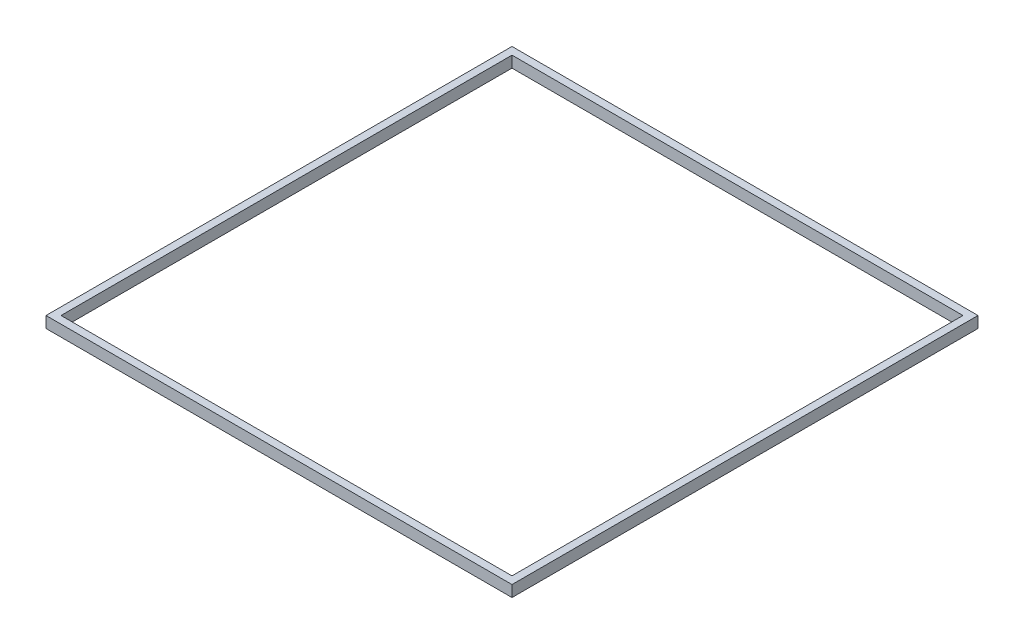
SolidWorks part; units mm, degrees
material "1060 Alloy"
ref_plane "Front Plane" through (0, 0, 0) normal (0, 0, 1) x (1, 0, 0)
ref_plane "Top Plane" through (0, 0, 0) normal (0, 1, 0) x (1, 0, 0)
ref_plane "Right Plane" through (0, 0, 0) normal (1, 0, 0) x (0, 0, -1)
sketch "Sketch1" plane through (0, 0, 0) normal (0, 1, 0) x (1, 0, 0)
  line L1 (-600, -600) -> (600, -600)
  line L2 (-600, -600) -> (-600, 600)
  line L3 (-600, 600) -> (600, 600)
  line L4 (600, -600) -> (600, 600)
  line L5 (-600, -600) -> (600, 600) construction
  line L6 (-600, 600) -> (600, -600) construction
  line L7 (-620, -620) -> (620, -620)
  line L8 (-620, -620) -> (-620, 620)
  line L9 (-620, 620) -> (620, 620)
  line L10 (620, -620) -> (620, 620)
  line L11 (-620, -620) -> (620, 620) construction
  line L12 (-620, 620) -> (620, -620) construction
  point P0 (0, 0)
  point P5 (0, 0)
  dimension "D1" = 20
  dimension "D2" = 20
  dimension "D3" = 1200
  dimension "D4" = 1200
extrude "Boss-Extrude1" add sketch "Sketch1" along normal mid plane 30
